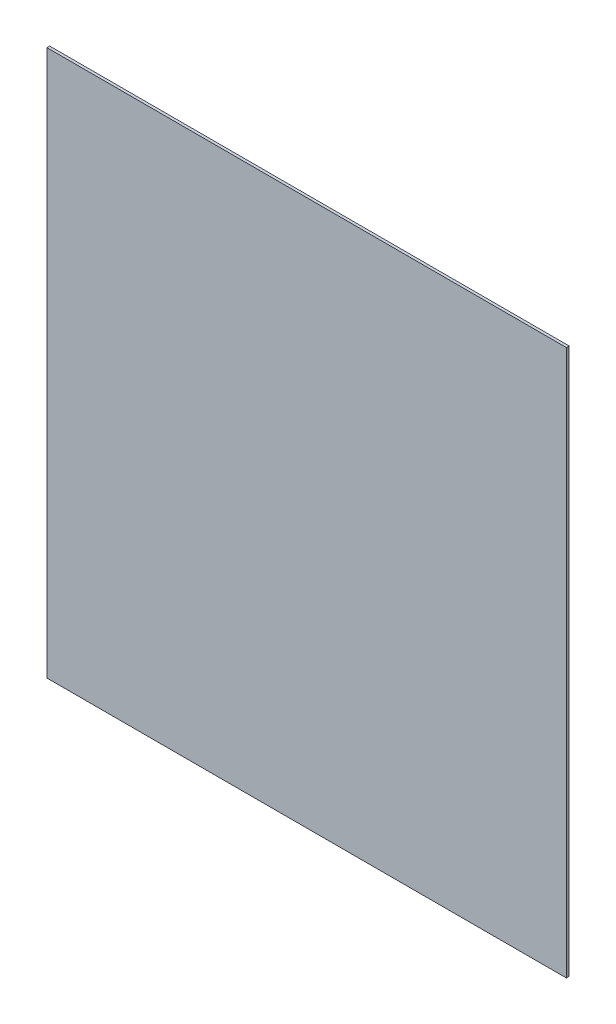
SolidWorks part; units mm, degrees
ref_plane "Front Plane" through (0, 0, 0) normal (0, 0, 1) x (1, 0, 0)
ref_plane "Top Plane" through (0, 0, 0) normal (0, 1, 0) x (1, 0, 0)
ref_plane "Right Plane" through (0, 0, 0) normal (1, 0, 0) x (0, 0, -1)
sketch "Sketch1" plane through (0, 0, 0) normal (0, 0, 1) x (1, 0, 0)
  line L1 (451.6604, -1008) -> (-500, -1008)
  line L2 (451.6604, -1008) -> (451.6604, -8)
  line L3 (451.6604, -8) -> (-500, -8)
  line L4 (-500, -1008) -> (-500, -8)
  line L5 (451.6604, -1008) -> (-500, -8) construction
  line L6 (451.6604, -8) -> (-500, -1008) construction
  point P0 (-24.1698, -508)
  dimension "D1" = 1000
extrude "Extrude1" add sketch "Sketch1" against normal blind 5
